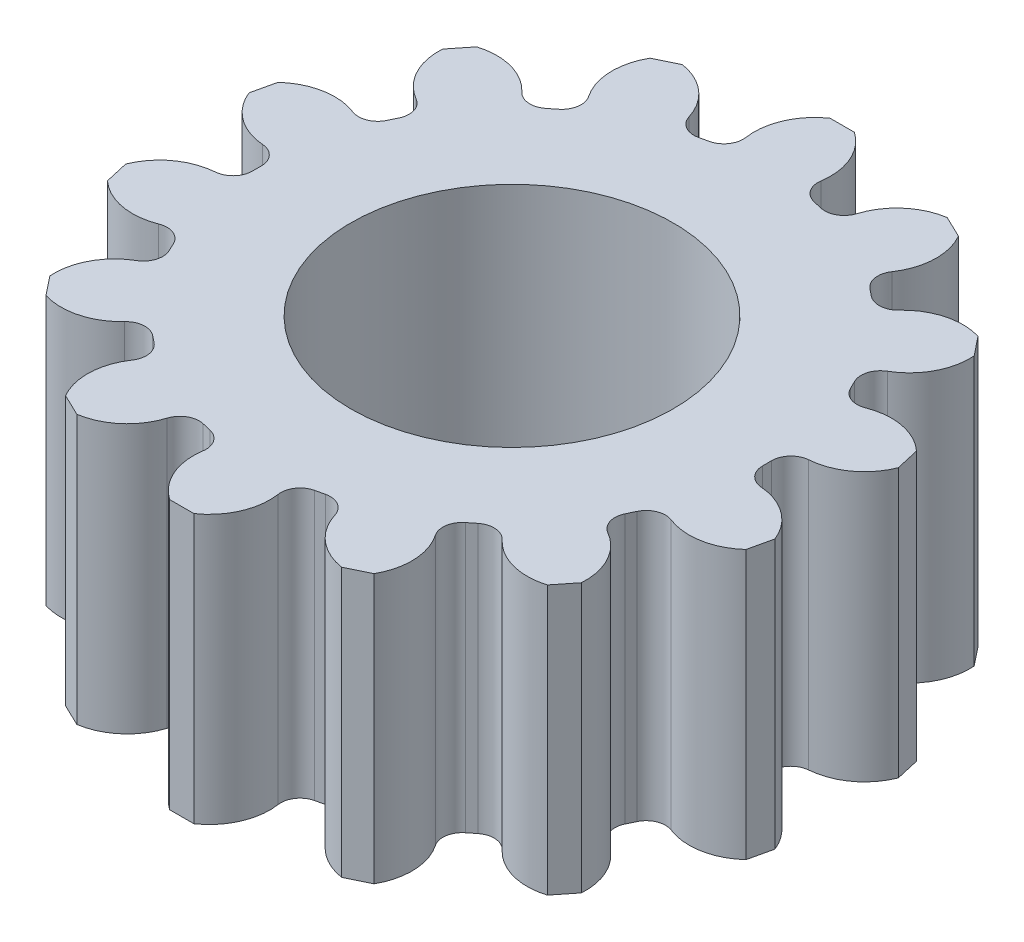
SolidWorks part; units mm, degrees
ref_plane "Front Plane" through (0, 0, 0) normal (0, 0, 1) x (1, 0, 0)
ref_plane "Top Plane" through (0, 0, 0) normal (0, 1, 0) x (1, 0, 0)
ref_plane "Right Plane" through (0, 0, 0) normal (1, 0, 0) x (0, 0, -1)
sketch "Sketch1" plane through (0, 0, 0) normal (0, 1, 0) x (1, 0, 0)
  line L0 (0, 6.1459) -> (0, 4.75) construction
  line L1 (-0.225, 6.1459) -> (0, 6.1459)
  line L2 (0.225, 6.1459) -> (0, 6.1459)
  line L3 (-0.975, 4.6489) -> (-1.1386, 4.6115)
  line L4 (1.1386, 4.6115) -> (0.975, 4.6489)
  line L5 (2.4639, 5.6349) -> (2.6666, 5.5372)
  line L6 (2.8693, 5.4396) -> (2.6666, 5.5372)
  line L7 (3.0267, 3.6608) -> (2.8955, 3.7654)
  line L8 (4.6648, 4.0078) -> (4.805, 3.8319)
  line L9 (4.9453, 3.656) -> (4.805, 3.8319)
  line L10 (4.3153, 1.985) -> (4.2425, 2.1362)
  line L11 (5.9417, 1.5869) -> (5.9918, 1.3676)
  line L12 (6.0419, 1.1482) -> (5.9918, 1.3676)
  line L13 (4.7493, -0.0839) -> (4.7493, 0.0839)
  line L14 (6.0419, -1.1482) -> (5.9918, -1.3676)
  line L15 (5.9417, -1.5869) -> (5.9918, -1.3676)
  line L16 (4.2425, -2.1362) -> (4.3153, -1.985)
  line L17 (4.9453, -3.656) -> (4.805, -3.8319)
  line L18 (4.6648, -4.0078) -> (4.805, -3.8319)
  line L19 (2.8955, -3.7654) -> (3.0267, -3.6608)
  line L20 (2.8693, -5.4396) -> (2.6666, -5.5372)
  line L21 (2.4639, -5.6349) -> (2.6666, -5.5372)
  line L22 (0.975, -4.6489) -> (1.1386, -4.6115)
  line L23 (0.225, -6.1459) -> (0, -6.1459)
  line L24 (-0.225, -6.1459) -> (0, -6.1459)
  line L25 (-1.1386, -4.6115) -> (-0.975, -4.6489)
  line L26 (-2.4639, -5.6349) -> (-2.6666, -5.5372)
  line L27 (-2.8693, -5.4396) -> (-2.6666, -5.5372)
  line L28 (-3.0267, -3.6608) -> (-2.8955, -3.7654)
  line L29 (-4.6648, -4.0078) -> (-4.805, -3.8319)
  line L30 (-4.9453, -3.656) -> (-4.805, -3.8319)
  line L31 (-4.3153, -1.985) -> (-4.2425, -2.1362)
  line L32 (-5.9417, -1.5869) -> (-5.9918, -1.3676)
  line L33 (-6.0419, -1.1482) -> (-5.9918, -1.3676)
  line L34 (-4.7493, 0.0839) -> (-4.7493, -0.0839)
  line L35 (-6.0419, 1.1482) -> (-5.9918, 1.3676)
  line L36 (-5.9417, 1.5869) -> (-5.9918, 1.3676)
  line L37 (-4.2425, 2.1362) -> (-4.3153, 1.985)
  line L38 (-4.9453, 3.656) -> (-4.805, 3.8319)
  line L39 (-4.6648, 4.0078) -> (-4.805, 3.8319)
  line L40 (-2.8955, 3.7654) -> (-3.0267, 3.6608)
  line L41 (-2.8693, 5.4396) -> (-2.6666, 5.5372)
  line L42 (-2.4639, 5.6349) -> (-2.6666, 5.5372)
  circle A0 centre (0, 0) radius 3
  circle A1 centre (0, 0) radius 5.5 construction
  circle A2 centre (0, 0) radius 5.1 construction
  circle A3 centre (0, 0) radius 6.15 construction
  arc A4 (-0.225, 6.1459) -> (-0.7, 5.0517) centre (0.4138, 5.2184) ccw
  circle A5 centre (0, 0) radius 4.75 construction
  arc A6 (-0.7, 5.0517) -> (-0.975, 4.6489) centre (-1.0548, 4.9986) cw
  arc A7 (0.7, 5.0517) -> (0.975, 4.6489) centre (1.0548, 4.9986) ccw
  arc A8 (0.225, 6.1459) -> (0.7, 5.0517) centre (-0.4138, 5.2184) cw
  arc A9 (1.5612, 4.8552) -> (1.1386, 4.6115) centre (1.2185, 4.9613) cw
  arc A10 (2.4639, 5.6349) -> (1.5612, 4.8552) centre (2.637, 4.522) ccw
  arc A11 (2.8693, 5.4396) -> (2.8225, 4.2477) centre (1.8913, 4.8811) cw
  arc A12 (2.8225, 4.2477) -> (2.8955, 3.7654) centre (3.1192, 4.0459) ccw
  arc A13 (3.5132, 3.697) -> (3.0267, 3.6608) centre (3.2504, 3.9413) cw
  arc A14 (4.6648, 4.0078) -> (3.5132, 3.697) centre (4.3379, 2.93) ccw
  arc A15 (4.9453, 3.656) -> (4.386, 2.6024) centre (3.8219, 3.5772) cw
  arc A16 (4.386, 2.6024) -> (4.2425, 2.1362) centre (4.5658, 2.2919) ccw
  arc A17 (4.7693, 1.8066) -> (4.3153, 1.985) centre (4.6386, 2.1407) cw
  arc A18 (5.9417, 1.5869) -> (4.7693, 1.8066) centre (5.1796, 0.7577) ccw
  arc A19 (6.0419, 1.1482) -> (5.0808, 0.4417) centre (4.9954, 1.5647) cw
  arc A20 (5.0808, 0.4417) -> (4.7493, 0.0839) centre (5.108, 0.0839) ccw
  arc A21 (5.0808, -0.4417) -> (4.7493, -0.0839) centre (5.108, -0.0839) cw
  arc A22 (6.0419, -1.1482) -> (5.0808, -0.4417) centre (4.9954, -1.5647) ccw
  arc A23 (5.9417, -1.5869) -> (4.7693, -1.8066) centre (5.1796, -0.7577) cw
  arc A24 (4.7693, -1.8066) -> (4.3153, -1.985) centre (4.6386, -2.1407) ccw
  arc A25 (4.386, -2.6024) -> (4.2425, -2.1362) centre (4.5658, -2.2919) cw
  arc A26 (4.9453, -3.656) -> (4.386, -2.6024) centre (3.8219, -3.5772) ccw
  arc A27 (4.6648, -4.0078) -> (3.5132, -3.697) centre (4.3379, -2.93) cw
  arc A28 (3.5132, -3.697) -> (3.0267, -3.6608) centre (3.2504, -3.9413) ccw
  arc A29 (2.8225, -4.2477) -> (2.8955, -3.7654) centre (3.1192, -4.0459) cw
  arc A30 (2.8693, -5.4396) -> (2.8225, -4.2477) centre (1.8913, -4.8811) ccw
  arc A31 (2.4639, -5.6349) -> (1.5612, -4.8552) centre (2.637, -4.522) cw
  arc A32 (1.5612, -4.8552) -> (1.1386, -4.6115) centre (1.2185, -4.9613) ccw
  arc A33 (0.7, -5.0517) -> (0.975, -4.6489) centre (1.0548, -4.9986) cw
  arc A34 (0.225, -6.1459) -> (0.7, -5.0517) centre (-0.4138, -5.2184) ccw
  arc A35 (-0.225, -6.1459) -> (-0.7, -5.0517) centre (0.4138, -5.2184) cw
  arc A36 (-0.7, -5.0517) -> (-0.975, -4.6489) centre (-1.0548, -4.9986) ccw
  arc A37 (-1.5612, -4.8552) -> (-1.1386, -4.6115) centre (-1.2185, -4.9613) cw
  arc A38 (-2.4639, -5.6349) -> (-1.5612, -4.8552) centre (-2.637, -4.522) ccw
  arc A39 (-2.8693, -5.4396) -> (-2.8225, -4.2477) centre (-1.8913, -4.8811) cw
  arc A40 (-2.8225, -4.2477) -> (-2.8955, -3.7654) centre (-3.1192, -4.0459) ccw
  arc A41 (-3.5132, -3.697) -> (-3.0267, -3.6608) centre (-3.2504, -3.9413) cw
  arc A42 (-4.6648, -4.0078) -> (-3.5132, -3.697) centre (-4.3379, -2.93) ccw
  arc A43 (-4.9453, -3.656) -> (-4.386, -2.6024) centre (-3.8219, -3.5772) cw
  arc A44 (-4.386, -2.6024) -> (-4.2425, -2.1362) centre (-4.5658, -2.2919) ccw
  arc A45 (-4.7693, -1.8066) -> (-4.3153, -1.985) centre (-4.6386, -2.1407) cw
  arc A46 (-5.9417, -1.5869) -> (-4.7693, -1.8066) centre (-5.1796, -0.7577) ccw
  arc A47 (-6.0419, -1.1482) -> (-5.0808, -0.4417) centre (-4.9954, -1.5647) cw
  arc A48 (-5.0808, -0.4417) -> (-4.7493, -0.0839) centre (-5.108, -0.0839) ccw
  arc A49 (-5.0808, 0.4417) -> (-4.7493, 0.0839) centre (-5.108, 0.0839) cw
  arc A50 (-6.0419, 1.1482) -> (-5.0808, 0.4417) centre (-4.9954, 1.5647) ccw
  arc A51 (-5.9417, 1.5869) -> (-4.7693, 1.8066) centre (-5.1796, 0.7577) cw
  arc A52 (-4.7693, 1.8066) -> (-4.3153, 1.985) centre (-4.6386, 2.1407) ccw
  arc A53 (-4.386, 2.6024) -> (-4.2425, 2.1362) centre (-4.5658, 2.2919) cw
  arc A54 (-4.9453, 3.656) -> (-4.386, 2.6024) centre (-3.8219, 3.5772) ccw
  arc A55 (-4.6648, 4.0078) -> (-3.5132, 3.697) centre (-4.3379, 2.93) cw
  arc A56 (-3.5132, 3.697) -> (-3.0267, 3.6608) centre (-3.2504, 3.9413) ccw
  arc A57 (-2.8225, 4.2477) -> (-2.8955, 3.7654) centre (-3.1192, 4.0459) cw
  arc A58 (-2.8693, 5.4396) -> (-2.8225, 4.2477) centre (-1.8913, 4.8811) ccw
  arc A59 (-2.4639, 5.6349) -> (-1.5612, 4.8552) centre (-2.637, 4.522) cw
  arc A60 (-1.5612, 4.8552) -> (-1.1386, 4.6115) centre (-1.2185, 4.9613) ccw
  point P19 (0, 0)
  point P20 (0, 0)
  point P21 (-0.2013, -7.9388)
  point P34 (0.322, -6.9933)
  point P46 (0, 0)
  point P58 (-0.5747, 8.6247)
  point P70 (0, 0)
  point P82 (0, 0)
  point P94 (-1.3599, 4.9154)
  point P106 (0, 0)
  point P118 (0, 0)
  point P130 (0, 0)
  dimension "D1" = 6
  dimension "D3" = 0.35
  dimension "D4" = 0.4
  dimension "D5" = 0.65
  dimension "D9" = 11
  dimension "D6" = 0.45
  dimension "D7" = 1.4
  dimension "D8" = 1.95
  dimension "D2" = 14
extrude "Boss-Extrude1" add sketch "Sketch1" along normal blind 5
